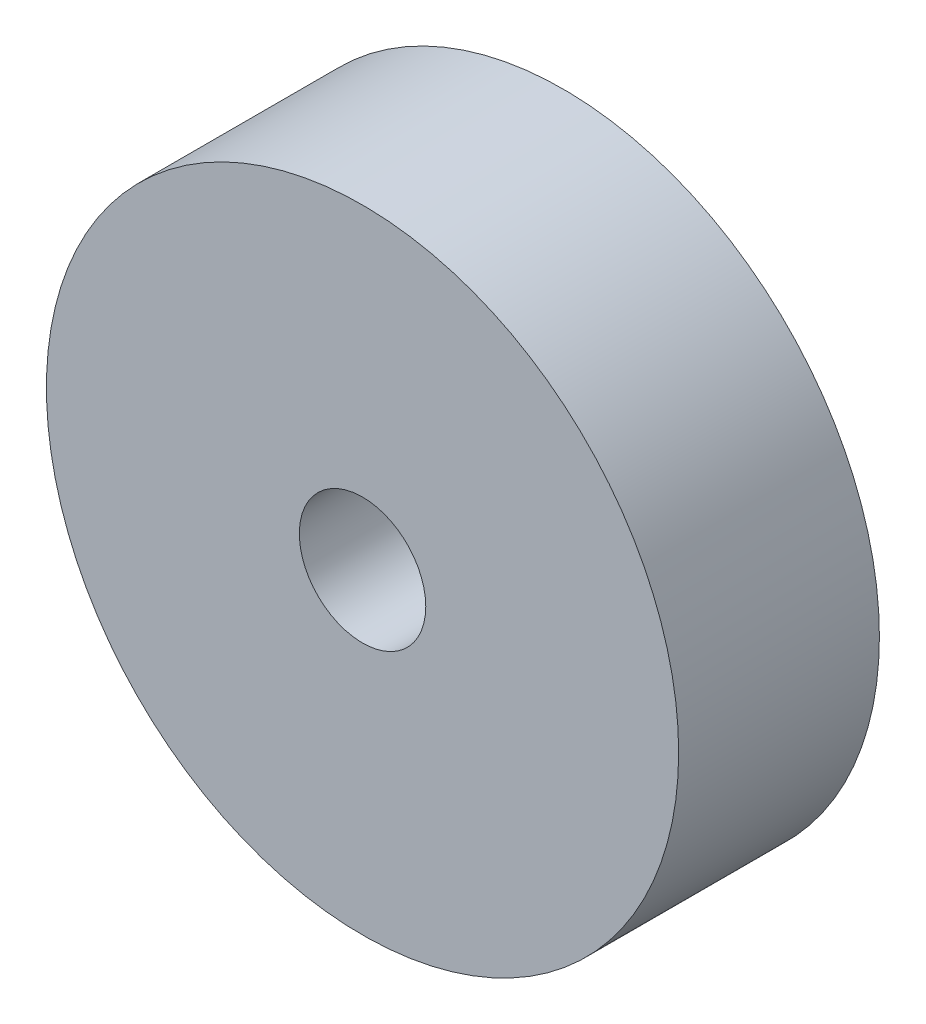
SolidWorks part; units mm, degrees
material "AISI 304"
ref_plane "Front Plane" through (0, 0, 0) normal (0, 0, 1) x (1, 0, 0)
ref_plane "Top Plane" through (0, 0, 0) normal (0, 1, 0) x (1, 0, 0)
ref_plane "Right Plane" through (0, 0, 0) normal (1, 0, 0) x (0, 0, -1)
sketch "Sketch1" plane through (0, 0, 0) normal (0, 0, 1) x (1, 0, 0)
  circle A0 centre (0, 0) radius 10
  circle A1 centre (0, 0) radius 2
  dimension "D1" = 20
extrude "Boss-Extrude1" add sketch "Sketch1" along normal blind 6.35
